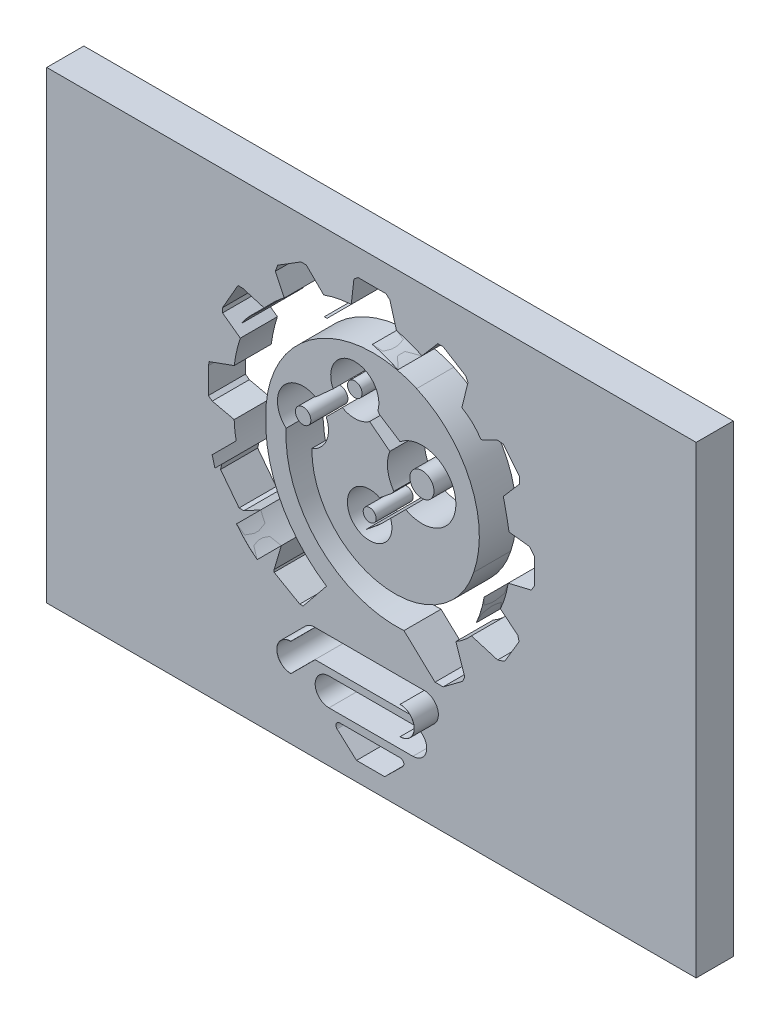
SolidWorks part; units mm, degrees
ref_plane "Front Plane" through (0, 0, 0) normal (0, 0, 1) x (1, 0, 0)
ref_plane "Top Plane" through (0, 0, 0) normal (0, 1, 0) x (1, 0, 0)
ref_plane "Right Plane" through (0, 0, 0) normal (1, 0, 0) x (0, 0, -1)
sketch "Sketch1" plane through (0, 0, 0) normal (0, 0, 1) x (1, 0, 0)
  line L0 (30.4571, 56.7891) -> (92.9051, 56.7891) construction
  line L1 (36.6127, 46.336) -> (66.0639, 46.336) construction
  line L8 (36.6127, 50.1281) -> (66.0639, 50.1281)
  line L11 (36.6127, 42.5438) -> (66.0639, 42.5438)
  line L12 (40.3711, 36.92) -> (62.9922, 36.92) construction
  line L15 (40.3711, 40.6319) -> (62.9922, 40.6319)
  line L16 (40.3711, 33.2082) -> (62.9922, 33.2082)
  line L17 (43.2916, 31.1455) -> (59.5488, 31.1455)
  line L20 (47.7936, 24.6426) -> (55.3803, 24.6426)
  line L21 (60.2553, 29.4313) -> (55.3803, 24.6426)
  line L22 (42.5548, 29.3665) -> (47.7936, 24.6426)
  line L23 (54.0424, 89.0572) -> (57.3383, 91.7453)
  line L24 (56.7754, 86.2384) -> (60.0907, 88.9424)
  line L25 (61.0672, 89.823) -> (60.0907, 88.9424)
  line L26 (57.8581, 92.482) -> (57.3383, 91.7453)
  line L27 (56.7753, 101.2636) -> (51.3382, 105.5029)
  line L28 (59.5486, 104.8905) -> (54.0422, 108.4233)
  line L29 (54.0422, 108.4233) -> (53.5429, 109.1547)
  line L30 (41.4931, 108.2048) -> (36.7513, 103.9283)
  line L31 (43.9752, 105.087) -> (39.6194, 100.7312)
  line L32 (60.5789, 61.3321) -> (68.9548, 53.4849)
  line L33 (71.1414, 53.4849) -> (76.4211, 57.4313)
  line L34 (76.4211, 57.4313) -> (76.9544, 58.7112)
  line L35 (68.9548, 53.4849) -> (71.1414, 53.4849)
  line L36 (76.9544, 58.7112) -> (74.5729, 65.7776)
  line L38 (78.7757, 69.2055) -> (85.8154, 67.0935)
  line L39 (85.8154, 67.0935) -> (87.7229, 67.7364)
  line L40 (87.7229, 67.7364) -> (91.598, 74.2278)
  line L41 (91.598, 74.2278) -> (91.2456, 75.6243)
  line L42 (91.2456, 75.6243) -> (86.565, 79.3976)
  line L44 (88.6833, 86.4585) -> (94.9099, 87.9467)
  line L45 (94.9099, 87.9467) -> (95.7671, 89.3827)
  line L46 (95.7671, 89.3827) -> (95.7671, 96.2119)
  line L47 (95.7671, 96.2119) -> (94.413, 97.8721)
  line L48 (94.413, 97.8721) -> (88.9053, 98.5005)
  line L50 (87.3603, 106.0456) -> (91.6591, 111.0252)
  line L51 (91.6591, 111.0252) -> (91.6591, 112.9758)
  line L52 (91.6591, 112.9758) -> (87.3603, 118.2186)
  line L53 (87.3603, 118.2186) -> (85.8154, 118.3949)
  line L54 (85.8154, 118.3949) -> (81.6957, 116.4107)
  line L55 (81.6957, 116.4107) -> (81.3263, 116.3111)
  line L56 (76.183, 121.1698) -> (77.8389, 127.8606)
  line L57 (77.8389, 127.8606) -> (77.2534, 129.0763)
  line L58 (77.2534, 129.0763) -> (71.1414, 132.8624)
  line L59 (71.1414, 132.8624) -> (69.7035, 132.8624)
  line L60 (69.7035, 132.8624) -> (65.4214, 127.8606)
  line L62 (58.5608, 130.3615) -> (56.7753, 136.6375)
  line L63 (56.7753, 136.6375) -> (55.7168, 137.5437)
  line L64 (55.7168, 137.5437) -> (48.205, 137.5437)
  line L65 (48.205, 137.5437) -> (47.0998, 136.6375)
  line L66 (47.0998, 136.6375) -> (46.3837, 130.3615)
  line L68 (38.9609, 128.8416) -> (34.2686, 133.4995)
  line L69 (34.2686, 133.4995) -> (32.8354, 133.4995)
  line L70 (32.8354, 133.4995) -> (26.5591, 129.6015)
  line L71 (26.5591, 129.6015) -> (25.9244, 127.8606)
  line L72 (25.9244, 127.8606) -> (28.3434, 122.8381)
  line L74 (23.3503, 117.6686) -> (17.1161, 119.5092)
  line L75 (17.1161, 119.5092) -> (15.8505, 119.5092)
  line L76 (15.8505, 119.5092) -> (11.7019, 112.2544)
  line L77 (11.7019, 112.2544) -> (11.7019, 111.0252)
  line L78 (11.7019, 111.0252) -> (16.4833, 107.5433)
  line L80 (14.8364, 100.3097) -> (8.1201, 97.8723)
  line L81 (8.1201, 97.8723) -> (7.8723, 96.7838)
  line L82 (7.8723, 96.7838) -> (7.8723, 89.823)
  line L83 (7.8723, 89.823) -> (8.924, 89.0572)
  line L84 (8.924, 89.0572) -> (14.8364, 87.7111)
  line L86 (16.1477, 80.2776) -> (11.4783, 75.6082)
  line L87 (11.4783, 75.6082) -> (11.164, 74.2278)
  line L88 (11.164, 74.2278) -> (16.1477, 67.7364)
  line L89 (16.1477, 67.7364) -> (17.4483, 67.7364)
  line L90 (17.4483, 67.7364) -> (21.968, 70.1863)
  line L92 (27.5295, 64.6248) -> (25.6004, 58.0911)
  line L93 (25.6004, 58.0911) -> (25.6004, 57.4313)
  line L94 (25.6004, 57.4313) -> (32.5018, 53.4849)
  line L95 (32.5018, 53.4849) -> (33.4122, 53.4849)
  line L96 (33.4122, 53.4849) -> (39.7262, 61.2639)
  arc A4 (36.6127, 50.1281) -> (36.6127, 42.5438) centre (36.6127, 46.336) ccw
  arc A5 (66.0639, 42.5438) -> (66.0639, 50.1281) centre (66.0639, 46.336) ccw
  arc A8 (40.3711, 40.6319) -> (40.3711, 33.2082) centre (40.3711, 36.92) ccw
  arc A9 (62.9922, 33.2082) -> (62.9922, 40.6319) centre (62.9922, 36.92) ccw
  arc A12 (60.2553, 29.4313) -> (59.5488, 31.1455) centre (59.5542, 30.145) ccw
  arc A13 (43.2916, 31.1455) -> (42.5548, 29.3665) centre (43.2916, 30.1034) ccw
  circle A14 centre (51.3383, 83.7011) radius 1.7357
  arc A16 (54.0424, 89.0572) -> (56.7754, 86.2384) centre (51.3383, 83.7011) ccw
  circle A17 centre (65.4214, 97.8721) radius 3.2539
  arc A18 (59.5486, 104.8905) -> (61.0672, 89.823) centre (65.4214, 97.8721) cw
  arc A19 (56.7753, 101.2636) -> (57.8581, 92.482) centre (65.4214, 97.8721) ccw
  circle A20 centre (47.3331, 111.0252) radius 1.9632
  arc A21 (53.5429, 109.1547) -> (41.4931, 108.2048) centre (47.3331, 111.0252) ccw
  arc A22 (51.3382, 105.5029) -> (43.9752, 105.087) centre (47.3331, 111.0252) cw
  circle A23 centre (33.4122, 97.8723) radius 2.0772
  arc A24 (36.7513, 103.9283) -> (28.8345, 92.6889) centre (33.4122, 97.8723) ccw
  arc A25 (39.6194, 100.7312) -> (35.7806, 91.462) centre (33.4122, 97.8723) cw
  arc A26 (28.8345, 92.6889) -> (60.5789, 61.3321) centre (58.5608, 91.0359) ccw
  arc A27 (35.7806, 91.462) -> (79.3675, 84.2956) centre (58.0912, 91.0243) ccw
  arc A28 (79.3675, 84.2956) -> (63.999, 119.5092) centre (52.423, 93.4965) ccw
  arc A29 (63.999, 119.5092) -> (23.3503, 92.7292) centre (52.2487, 93.1048) ccw
  arc A30 (39.7262, 61.2639) -> (23.3503, 92.7292) centre (59.3064, 91.4483) cw
  arc A33 (16.4833, 107.5433) -> (14.8364, 100.3097) centre (52.4804, 95.5437) ccw
  spline S0 degree 2 poles (14.8364, 87.7111) (14.97, 83.7216) (16.1477, 80.2776) knots 0 0 0 1 1 1
  spline S1 degree 2 poles (27.5295, 64.6248) (24.5135, 66.8639) (21.968, 70.1863) knots 0 0 0 1 1 1
  spline S2 degree 2 poles (28.3434, 122.8381) (25.0832, 120.5414) (23.3503, 117.6686) knots 0 0 0 1 1 1
  spline S3 degree 2 poles (46.3837, 130.3615) (43.2077, 130.1934) (38.9609, 128.8416) knots 0 0 0 1 1 1
  spline S4 degree 2 poles (65.4214, 127.8606) (62.7623, 129.3468) (58.5608, 130.3615) knots 0 0 0 1 1 1
  spline S5 degree 2 poles (76.183, 121.1698) (79.2538, 119.4133) (81.3263, 116.3111) knots 0 0 0 1 1 1
  spline S6 degree 1 poles (87.3603, 106.0456) (88.9053, 98.5005) knots 0 0 1 1
  spline S7 degree 2 poles (88.6833, 86.4585) (88.1006, 82.7484) (86.565, 79.3976) knots 0 0 0 1 1 1
  spline S8 degree 2 poles (78.7757, 69.2055) (76.889, 67.188) (74.5729, 65.7776) knots 0 0 0 1 1 1
  point P4 (51.3383, 46.336)
  point P12 (51.6817, 36.92)
extrude "Boss-Extrude1" add sketch "Sketch1" along normal blind 10
sketch "Sketch2" plane through (0, 0, 0) normal (0, 0, -1) x (-1, 0, 0)
  line L1 (-54.14, 86.5559) -> (-58.8145, 90.3685)
  line L2 (-58.8145, 90.3685) -> (-60.3896, 92.6007)
  line L3 (-59.3021, 101.8295) -> (-51.2009, 108.146)
  line L4 (-43.8018, 107.742) -> (-37.0804, 101.0206)
  line L5 (-36.8123, 60.8475) -> (-32.6415, 55.7089)
  line L6 (-32.6415, 55.7089) -> (-32.6415, 55.7089)
  line L7 (-32.6415, 55.7089) -> (-27.7999, 58.4775)
  line L8 (-27.7999, 58.4775) -> (-27.7999, 58.4775)
  line L9 (-27.7999, 58.4775) -> (-29.8561, 65.442)
  line L10 (-22.5558, 72.7799) -> (-17.077, 69.8101)
  line L11 (-17.077, 69.8101) -> (-17.077, 69.8101)
  line L12 (-17.077, 69.8101) -> (-13.3557, 74.6573)
  line L13 (-13.3557, 74.6573) -> (-13.3557, 74.6573)
  line L14 (-13.3557, 74.6573) -> (-18.4724, 79.7739)
  line L15 (-16.8248, 89.3096) -> (-9.8723, 90.8925)
  line L16 (-9.8723, 90.8925) -> (-9.8723, 90.8925)
  line L17 (-9.8723, 90.8925) -> (-9.8723, 96.3806)
  line L18 (-9.8723, 96.3806) -> (-9.8723, 96.3806)
  line L19 (-9.8723, 96.3806) -> (-16.6887, 98.8543)
  line L20 (-18.8683, 108.2807) -> (-13.8311, 111.9488)
  line L21 (-13.8311, 111.9488) -> (-13.8311, 111.9488)
  line L22 (-13.8311, 111.9488) -> (-16.9842, 117.4628)
  line L23 (-16.9842, 117.4628) -> (-16.9842, 117.4628)
  line L24 (-16.9842, 117.4628) -> (-24.3628, 115.2843)
  line L25 (-30.9081, 122.1222) -> (-28.0924, 127.9683)
  line L26 (-28.0924, 127.9683) -> (-28.2014, 128.2672)
  line L27 (-28.2014, 128.2672) -> (-33.4059, 131.4995)
  line L28 (-33.4059, 131.4995) -> (-33.4444, 131.4995)
  line L29 (-33.4444, 131.4995) -> (-38.424, 126.5564)
  line L30 (-48.1674, 128.3526) -> (-48.988, 135.5437)
  line L31 (-48.988, 135.5437) -> (-48.988, 135.5437)
  line L32 (-48.988, 135.5437) -> (-54.9776, 135.5437)
  line L33 (-54.9776, 135.5437) -> (-55.0166, 135.5103)
  line L34 (-55.0166, 135.5103) -> (-56.9612, 128.6751)
  line L35 (-65.8037, 125.2318) -> (-70.6061, 130.8413)
  line L36 (-70.6061, 130.8413) -> (-70.6061, 130.8413)
  line L37 (-70.6061, 130.8413) -> (-75.7045, 127.6831)
  line L38 (-75.7045, 127.6831) -> (-75.7244, 127.6418)
  line L39 (-75.7244, 127.6418) -> (-73.8578, 120.0996)
  line L40 (-80.3979, 113.9894) -> (-82.3959, 114.5281)
  line L41 (-82.3959, 114.5281) -> (-86.1627, 116.3423)
  line L42 (-86.1627, 116.3423) -> (-86.3279, 116.3234)
  line L43 (-86.3279, 116.3234) -> (-89.6591, 112.2607)
  line L44 (-89.6591, 112.2607) -> (-89.6591, 111.769)
  line L45 (-89.6591, 111.769) -> (-85.2037, 106.608)
  line L46 (-85.2037, 106.608) -> (-87.237, 96.6779)
  line L47 (-87.237, 96.6779) -> (-93.3776, 95.9772)
  line L48 (-93.3776, 95.9772) -> (-93.7671, 95.4997)
  line L49 (-93.7671, 95.4997) -> (-93.7671, 89.9342)
  line L50 (-93.7671, 89.9342) -> (-93.6248, 89.6959)
  line L51 (-93.6248, 89.6959) -> (-86.8806, 88.0839)
  line L52 (-84.0603, 78.8479) -> (-89.4385, 74.5121)
  line L53 (-89.4385, 74.5121) -> (-89.4385, 74.5121)
  line L54 (-89.4385, 74.5121) -> (-86.3843, 69.3958)
  line L55 (-86.3843, 69.3958) -> (-85.7801, 69.1922)
  line L56 (-85.7801, 69.1922) -> (-78.1209, 71.49)
  line L57 (-72.1441, 66.722) -> (-74.8187, 58.7857)
  line L58 (-74.8187, 58.7857) -> (-74.7854, 58.7056)
  line L59 (-74.7854, 58.7056) -> (-70.4765, 55.4849)
  line L60 (-70.4765, 55.4849) -> (-69.7453, 55.4849)
  line L61 (-69.7453, 55.4849) -> (-61.2981, 63.3988)
  line L62 (-36.8826, 101.3536) -> (-44.1277, 107.8876)
  line L63 (-51.2885, 108.91) -> (-52.6198, 106.9596)
  line L64 (-52.6198, 106.9596) -> (-59.8316, 102.3327)
  line L65 (-60.8803, 92.3476) -> (-58.7881, 90.4609)
  line L66 (-58.7881, 90.4609) -> (-54.0759, 86.6175)
  line L67 (-54.0424, 89.0572) -> (-57.3383, 91.7453)
  line L68 (-57.3383, 91.7453) -> (-57.8581, 92.482)
  line L69 (-56.7753, 101.2636) -> (-51.3382, 105.5029)
  line L70 (-43.9752, 105.087) -> (-39.6194, 100.7312)
  line L71 (-39.7262, 61.2639) -> (-33.4122, 53.4849)
  line L72 (-33.4122, 53.4849) -> (-32.5018, 53.4849)
  line L73 (-32.5018, 53.4849) -> (-25.6004, 57.4313)
  line L74 (-25.6004, 57.4313) -> (-25.6004, 58.0911)
  line L75 (-25.6004, 58.0911) -> (-27.5295, 64.6248)
  line L76 (-21.968, 70.1863) -> (-17.4483, 67.7364)
  line L77 (-17.4483, 67.7364) -> (-16.1477, 67.7364)
  line L78 (-16.1477, 67.7364) -> (-11.164, 74.2278)
  line L79 (-11.164, 74.2278) -> (-11.4783, 75.6082)
  line L80 (-11.4783, 75.6082) -> (-16.1477, 80.2776)
  line L81 (-14.8364, 87.7111) -> (-8.924, 89.0572)
  line L82 (-8.924, 89.0572) -> (-7.8723, 89.823)
  line L83 (-7.8723, 89.823) -> (-7.8723, 96.7838)
  line L84 (-7.8723, 96.7838) -> (-8.1201, 97.8723)
  line L85 (-8.1201, 97.8723) -> (-14.8364, 100.3097)
  line L86 (-16.4833, 107.5433) -> (-11.7019, 111.0252)
  line L87 (-11.7019, 111.0252) -> (-11.7019, 112.2544)
  line L88 (-11.7019, 112.2544) -> (-15.8505, 119.5092)
  line L89 (-15.8505, 119.5092) -> (-17.1161, 119.5092)
  line L90 (-17.1161, 119.5092) -> (-23.3503, 117.6686)
  line L91 (-28.3434, 122.8381) -> (-25.9244, 127.8606)
  line L92 (-25.9244, 127.8606) -> (-26.5591, 129.6015)
  line L93 (-26.5591, 129.6015) -> (-32.8354, 133.4995)
  line L94 (-32.8354, 133.4995) -> (-34.2686, 133.4995)
  line L95 (-34.2686, 133.4995) -> (-38.9609, 128.8416)
  line L96 (-46.3837, 130.3615) -> (-47.0998, 136.6375)
  line L97 (-47.0998, 136.6375) -> (-48.205, 137.5437)
  line L98 (-48.205, 137.5437) -> (-55.7168, 137.5437)
  line L99 (-55.7168, 137.5437) -> (-56.7753, 136.6375)
  line L100 (-56.7753, 136.6375) -> (-58.5608, 130.3615)
  line L101 (-65.4214, 127.8606) -> (-69.7035, 132.8624)
  line L102 (-69.7035, 132.8624) -> (-71.1414, 132.8624)
  line L103 (-71.1414, 132.8624) -> (-77.2534, 129.0763)
  line L104 (-77.2534, 129.0763) -> (-77.8389, 127.8606)
  line L105 (-77.8389, 127.8606) -> (-76.183, 121.1698)
  line L106 (-81.3263, 116.3111) -> (-81.6957, 116.4107)
  line L107 (-81.6957, 116.4107) -> (-85.8154, 118.3949)
  line L108 (-85.8154, 118.3949) -> (-87.3603, 118.2186)
  line L109 (-87.3603, 118.2186) -> (-91.6591, 112.9758)
  line L110 (-91.6591, 112.9758) -> (-91.6591, 111.0252)
  line L111 (-91.6591, 111.0252) -> (-87.3603, 106.0456)
  line L112 (-87.3603, 106.0456) -> (-88.9053, 98.5005)
  line L113 (-88.9053, 98.5005) -> (-94.413, 97.8721)
  line L114 (-94.413, 97.8721) -> (-95.7671, 96.2119)
  line L115 (-95.7671, 96.2119) -> (-95.7671, 89.3827)
  line L116 (-95.7671, 89.3827) -> (-94.9099, 87.9467)
  line L117 (-94.9099, 87.9467) -> (-88.6833, 86.4585)
  line L118 (-86.565, 79.3976) -> (-91.2456, 75.6243)
  line L119 (-91.2456, 75.6243) -> (-91.598, 74.2278)
  line L120 (-91.598, 74.2278) -> (-87.7229, 67.7364)
  line L121 (-87.7229, 67.7364) -> (-85.8154, 67.0935)
  line L122 (-85.8154, 67.0935) -> (-78.7757, 69.2055)
  line L123 (-74.5729, 65.7776) -> (-76.9544, 58.7112)
  line L124 (-76.9544, 58.7112) -> (-76.4211, 57.4313)
  line L125 (-76.4211, 57.4313) -> (-71.1414, 53.4849)
  line L126 (-71.1414, 53.4849) -> (-68.9548, 53.4849)
  line L127 (-68.9548, 53.4849) -> (-60.5789, 61.3321)
  line L128 (-36.7513, 103.9283) -> (-41.4931, 108.2048)
  line L129 (-53.5429, 109.1547) -> (-54.0422, 108.4233)
  line L130 (-54.0422, 108.4233) -> (-59.5486, 104.8905)
  line L131 (-61.0672, 89.823) -> (-60.0907, 88.9424)
  line L132 (-60.0907, 88.9424) -> (-56.7754, 86.2384)
  line L133 (-54.0424, 89.0572) -> (-57.3383, 91.7453)
  line L134 (-57.3383, 91.7453) -> (-57.8581, 92.482)
  line L135 (-56.7753, 101.2636) -> (-51.3382, 105.5029)
  line L136 (-43.9752, 105.087) -> (-39.6194, 100.7312)
  line L137 (-39.7262, 61.2639) -> (-33.4122, 53.4849)
  line L138 (-33.4122, 53.4849) -> (-32.5018, 53.4849)
  line L139 (-32.5018, 53.4849) -> (-25.6004, 57.4313)
  line L140 (-25.6004, 57.4313) -> (-25.6004, 58.0911)
  line L141 (-25.6004, 58.0911) -> (-27.5295, 64.6248)
  line L142 (-21.968, 70.1863) -> (-17.4483, 67.7364)
  line L143 (-17.4483, 67.7364) -> (-16.1477, 67.7364)
  line L144 (-16.1477, 67.7364) -> (-11.164, 74.2278)
  line L145 (-11.164, 74.2278) -> (-11.4783, 75.6082)
  line L146 (-11.4783, 75.6082) -> (-16.1477, 80.2776)
  line L147 (-14.8364, 87.7111) -> (-8.924, 89.0572)
  line L148 (-8.924, 89.0572) -> (-7.8723, 89.823)
  line L149 (-7.8723, 89.823) -> (-7.8723, 96.7838)
  line L150 (-7.8723, 96.7838) -> (-8.1201, 97.8723)
  line L151 (-8.1201, 97.8723) -> (-14.8364, 100.3097)
  line L152 (-16.4833, 107.5433) -> (-11.7019, 111.0252)
  line L153 (-11.7019, 111.0252) -> (-11.7019, 112.2544)
  line L154 (-11.7019, 112.2544) -> (-15.8505, 119.5092)
  line L155 (-15.8505, 119.5092) -> (-17.1161, 119.5092)
  line L156 (-17.1161, 119.5092) -> (-23.3503, 117.6686)
  line L157 (-28.3434, 122.8381) -> (-25.9244, 127.8606)
  line L158 (-25.9244, 127.8606) -> (-26.5591, 129.6015)
  line L159 (-26.5591, 129.6015) -> (-32.8354, 133.4995)
  line L160 (-32.8354, 133.4995) -> (-34.2686, 133.4995)
  line L161 (-34.2686, 133.4995) -> (-38.9609, 128.8416)
  line L162 (-46.3837, 130.3615) -> (-47.0998, 136.6375)
  line L163 (-47.0998, 136.6375) -> (-48.205, 137.5437)
  line L164 (-48.205, 137.5437) -> (-55.7168, 137.5437)
  line L165 (-55.7168, 137.5437) -> (-56.7753, 136.6375)
  line L166 (-56.7753, 136.6375) -> (-58.5608, 130.3615)
  line L167 (-65.4214, 127.8606) -> (-69.7035, 132.8624)
  line L168 (-69.7035, 132.8624) -> (-71.1414, 132.8624)
  line L169 (-71.1414, 132.8624) -> (-77.2534, 129.0763)
  line L170 (-77.2534, 129.0763) -> (-77.8389, 127.8606)
  line L171 (-77.8389, 127.8606) -> (-76.183, 121.1698)
  line L172 (-81.3263, 116.3111) -> (-81.6957, 116.4107)
  line L173 (-81.6957, 116.4107) -> (-85.8154, 118.3949)
  line L174 (-85.8154, 118.3949) -> (-87.3603, 118.2186)
  line L175 (-87.3603, 118.2186) -> (-91.6591, 112.9758)
  line L176 (-91.6591, 112.9758) -> (-91.6591, 111.0252)
  line L177 (-91.6591, 111.0252) -> (-87.3603, 106.0456)
  line L178 (-87.3603, 106.0456) -> (-88.9053, 98.5005)
  line L179 (-88.9053, 98.5005) -> (-94.413, 97.8721)
  line L180 (-94.413, 97.8721) -> (-95.7671, 96.2119)
  line L181 (-95.7671, 96.2119) -> (-95.7671, 89.3827)
  line L182 (-95.7671, 89.3827) -> (-94.9099, 87.9467)
  line L183 (-94.9099, 87.9467) -> (-88.6833, 86.4585)
  line L184 (-86.565, 79.3976) -> (-91.2456, 75.6243)
  line L185 (-91.2456, 75.6243) -> (-91.598, 74.2278)
  line L186 (-91.598, 74.2278) -> (-87.7229, 67.7364)
  line L187 (-87.7229, 67.7364) -> (-85.8154, 67.0935)
  line L188 (-85.8154, 67.0935) -> (-78.7757, 69.2055)
  line L189 (-74.5729, 65.7776) -> (-76.9544, 58.7112)
  line L190 (-76.9544, 58.7112) -> (-76.4211, 57.4313)
  line L191 (-76.4211, 57.4313) -> (-71.1414, 53.4849)
  line L192 (-71.1414, 53.4849) -> (-68.9548, 53.4849)
  line L193 (-68.9548, 53.4849) -> (-60.5789, 61.3321)
  line L194 (-36.7513, 103.9283) -> (-41.4931, 108.2048)
  line L195 (-53.5429, 109.1547) -> (-54.0422, 108.4233)
  line L196 (-54.0422, 108.4233) -> (-59.5486, 104.8905)
  line L197 (-61.0672, 89.823) -> (-60.0907, 88.9424)
  line L198 (-60.0907, 88.9424) -> (-56.7754, 86.2384)
  arc A0 (-54.0759, 86.6175) -> (-54.14, 86.5559) centre (-51.3383, 83.7011) ccw
  arc A1 (-60.3896, 92.6007) -> (-59.3021, 101.8295) centre (-65.4214, 97.8721) ccw
  arc A2 (-51.2009, 108.146) -> (-43.8018, 107.742) centre (-47.3331, 111.0252) ccw
  arc A3 (-37.0804, 101.0206) -> (-33.8616, 93.0594) centre (-33.4122, 97.8723) ccw
  arc A4 (-81.2676, 83.6708) -> (-33.8616, 93.0594) centre (-58.0912, 91.0243) ccw
  arc A5 (-64.8122, 121.3364) -> (-81.2676, 83.6708) centre (-52.423, 93.4965) ccw
  arc A6 (-21.3499, 92.752) -> (-64.8122, 121.3364) centre (-52.2487, 93.1048) ccw
  arc A7 (-36.8123, 60.8475) -> (-21.3499, 92.752) centre (-59.3064, 91.4483) ccw
  arc A8 (-16.6887, 98.8543) -> (-18.8683, 108.2807) centre (-52.4804, 95.5437) ccw
  arc A9 (-61.2981, 63.3988) -> (-30.911, 93.6408) centre (-58.5608, 91.0359) ccw
  arc A10 (-30.911, 93.6408) -> (-36.8826, 101.3536) centre (-33.4122, 97.8723) ccw
  arc A11 (-44.1277, 107.8876) -> (-51.2885, 108.91) centre (-47.3331, 111.0252) ccw
  arc A12 (-59.8316, 102.3327) -> (-60.8803, 92.3476) centre (-65.4214, 97.8721) ccw
  arc A13 (-56.7754, 86.2384) -> (-54.0424, 89.0572) centre (-51.3383, 83.7011) ccw
  arc A14 (-57.8581, 92.482) -> (-56.7753, 101.2636) centre (-65.4214, 97.8721) ccw
  arc A15 (-51.3382, 105.5029) -> (-43.9752, 105.087) centre (-47.3331, 111.0252) ccw
  arc A16 (-39.6194, 100.7312) -> (-35.7806, 91.462) centre (-33.4122, 97.8723) ccw
  arc A17 (-79.3675, 84.2956) -> (-35.7806, 91.462) centre (-58.0912, 91.0243) ccw
  arc A18 (-63.999, 119.5092) -> (-79.3675, 84.2956) centre (-52.423, 93.4965) ccw
  arc A19 (-23.3503, 92.7292) -> (-63.999, 119.5092) centre (-52.2487, 93.1048) ccw
  arc A20 (-39.7262, 61.2639) -> (-23.3503, 92.7292) centre (-59.3064, 91.4483) ccw
  arc A21 (-14.8364, 100.3097) -> (-16.4833, 107.5433) centre (-52.4804, 95.5437) ccw
  arc A22 (-60.5789, 61.3321) -> (-28.8345, 92.6889) centre (-58.5608, 91.0359) ccw
  arc A23 (-28.8345, 92.6889) -> (-36.7513, 103.9283) centre (-33.4122, 97.8723) ccw
  arc A24 (-41.4931, 108.2048) -> (-53.5429, 109.1547) centre (-47.3331, 111.0252) ccw
  arc A25 (-59.5486, 104.8905) -> (-61.0672, 89.823) centre (-65.4214, 97.8721) ccw
  arc A26 (-56.7754, 86.2384) -> (-54.0424, 89.0572) centre (-51.3383, 83.7011) ccw
  arc A27 (-57.8581, 92.482) -> (-56.7753, 101.2636) centre (-65.4214, 97.8721) ccw
  arc A28 (-51.3382, 105.5029) -> (-43.9752, 105.087) centre (-47.3331, 111.0252) ccw
  arc A29 (-39.6194, 100.7312) -> (-35.7806, 91.462) centre (-33.4122, 97.8723) ccw
  arc A30 (-79.3675, 84.2956) -> (-35.7806, 91.462) centre (-58.0912, 91.0243) ccw
  arc A31 (-63.999, 119.5092) -> (-79.3675, 84.2956) centre (-52.423, 93.4965) ccw
  arc A32 (-23.3503, 92.7292) -> (-63.999, 119.5092) centre (-52.2487, 93.1048) ccw
  arc A33 (-39.7262, 61.2639) -> (-23.3503, 92.7292) centre (-59.3064, 91.4483) ccw
  arc A34 (-14.8364, 100.3097) -> (-16.4833, 107.5433) centre (-52.4804, 95.5437) ccw
  arc A35 (-60.5789, 61.3321) -> (-28.8345, 92.6889) centre (-58.5608, 91.0359) ccw
  arc A36 (-28.8345, 92.6889) -> (-36.7513, 103.9283) centre (-33.4122, 97.8723) ccw
  arc A37 (-41.4931, 108.2048) -> (-53.5429, 109.1547) centre (-47.3331, 111.0252) ccw
  arc A38 (-59.5486, 104.8905) -> (-61.0672, 89.823) centre (-65.4214, 97.8721) ccw
  parabola Q8 (-27.5295, 64.6248) -> (-21.968, 70.1863) focus (-36.6411, 72.3496) apex (-32.1285, 61.957)
  parabola Q9 (-16.1477, 80.2776) -> (-14.8364, 87.7111) focus (-27.2163, 82.2633) apex (-17.4778, 77.1751)
  parabola Q10 (-23.3503, 117.6686) -> (-28.3434, 122.8381) focus (-28.5124, 113.0969) apex (-22.2722, 115.4509)
  parabola Q11 (-38.9609, 128.8416) -> (-46.3837, 130.3615) focus (-51.1069, 126.1376) apex (-53.2201, 128.4735)
  parabola Q12 (-58.5608, 130.3615) -> (-65.4214, 127.8606) focus (-66.8713, 122.2923) apex (-69.7381, 123.1689)
  parabola Q13 (-76.183, 121.1698) -> (-81.3263, 116.3111) focus (-73.2684, 114.293) apex (-77.656, 120.2074)
  parabola Q14 (-88.6833, 86.4585) -> (-86.565, 79.3976) focus (-74.8514, 85.7796) apex (-87.2732, 81.0955)
  parabola Q15 (-78.7757, 69.2055) -> (-74.5729, 65.7776) focus (-70.0201, 74.5575) apex (-75.7041, 66.5208)
  parabola Q16 (-27.5295, 64.6248) -> (-21.968, 70.1863) focus (-36.6411, 72.3496) apex (-32.1285, 61.957)
  parabola Q17 (-16.1477, 80.2776) -> (-14.8364, 87.7111) focus (-27.2163, 82.2633) apex (-17.4778, 77.1751)
  parabola Q18 (-23.3503, 117.6686) -> (-28.3434, 122.8381) focus (-28.5124, 113.0969) apex (-22.2722, 115.4509)
  parabola Q19 (-38.9609, 128.8416) -> (-46.3837, 130.3615) focus (-51.1069, 126.1376) apex (-53.2201, 128.4735)
  parabola Q20 (-58.5608, 130.3615) -> (-65.4214, 127.8606) focus (-66.8713, 122.2923) apex (-69.7381, 123.1689)
  parabola Q21 (-76.183, 121.1698) -> (-81.3263, 116.3111) focus (-73.2684, 114.293) apex (-77.656, 120.2074)
  parabola Q22 (-88.6833, 86.4585) -> (-86.565, 79.3976) focus (-74.8514, 85.7796) apex (-87.2732, 81.0955)
  parabola Q23 (-78.7757, 69.2055) -> (-74.5729, 65.7776) focus (-70.0201, 74.5575) apex (-75.7041, 66.5208)
  spline S0 degree 1 poles (-29.8561, 65.442) (-22.5558, 72.7799) knots 0 0 1 1 construction
  spline S1 degree 1 poles (-18.4724, 79.7739) (-16.8248, 89.3096) knots 0 0 1 1 construction
  spline S2 degree 1 poles (-24.3628, 115.2843) (-30.9081, 122.1222) knots 0 0 1 1 construction
  spline S3 degree 1 poles (-38.424, 126.5564) (-48.1674, 128.3526) knots 0 0 1 1 construction
  spline S4 degree 1 poles (-56.9612, 128.6751) (-65.8037, 125.2318) knots 0 0 1 1 construction
  spline S5 degree 1 poles (-73.8578, 120.0996) (-80.3979, 113.9894) knots 0 0 1 1 construction
  spline S6 degree 1 poles (-86.8806, 88.0839) (-84.0603, 78.8479) knots 0 0 1 1 construction
  spline S7 degree 1 poles (-78.1209, 71.49) (-72.1441, 66.722) knots 0 0 1 1 construction
  spline S8 degree 3 poles (-29.8561, 65.442) (-29.1755, 65.884) (-27.8791, 66.8318) (-26.0024, 68.5312) (-24.5199, 70.1696) (-23.3838, 71.612) (-22.8245, 72.3896) (-22.5558, 72.7799) knots 0.500282 0.500282 0.500282 0.500282 0.500475 0.500667 0.500859 0.500955 0.501051 0.501051 0.501051 0.501051
  spline S9 degree 3 poles (-18.4724, 79.7739) (-18.1809, 80.4842) (-17.6821, 81.9251) (-17.1525, 84.2374) (-16.9031, 86.281) (-16.8191, 87.9836) (-16.8164, 88.8707) (-16.8248, 89.3096) knots 0.500153 0.500153 0.500153 0.500153 0.500341 0.50053 0.500718 0.500812 0.500906 0.500906 0.500906 0.500906
  spline S10 degree 3 poles (-24.3628, 115.2843) (-24.6467, 115.9337) (-25.3222, 117.1593) (-26.735, 118.9215) (-28.2635, 120.3079) (-29.6944, 121.3595) (-30.5042, 121.879) (-30.9081, 122.1222) knots 0.500066 0.500066 0.500066 0.500066 0.500305 0.500543 0.500781 0.5009 0.501019 0.501019 0.501019 0.501019
  spline S11 degree 3 poles (-38.424, 126.5564) (-38.9237, 126.7287) (-39.9513, 127.0654) (-41.8435, 127.6142) (-44.0285, 128.1106) (-45.9197, 128.35) (-47.2723, 128.3963) (-47.8625, 128.3756) (-48.1674, 128.3526) knots 0.498389 0.498389 0.498389 0.498389 0.498504 0.498619 0.49885 0.49908 0.499196 0.499311 0.499311 0.499311 0.499311
  spline S12 degree 3 poles (-56.9612, 128.6751) (-57.464, 128.5668) (-58.4903, 128.3285) (-60.3332, 127.8285) (-62.3772, 127.1332) (-64.0252, 126.3705) (-65.1246, 125.7212) (-65.5766, 125.4058) (-65.8037, 125.2318) knots 0.498448 0.498448 0.498448 0.498448 0.498565 0.498681 0.498915 0.499148 0.499264 0.499381 0.499381 0.499381 0.499381
  spline S13 degree 3 poles (-73.8578, 120.0996) (-74.5416, 119.8034) (-75.8747, 119.0902) (-77.5953, 117.7419) (-78.8646, 116.3448) (-79.7724, 115.063) (-80.2001, 114.3485) (-80.3979, 113.9894) knots 0.499683 0.499683 0.499683 0.499683 0.499917 0.500152 0.500386 0.500504 0.500621 0.500621 0.500621 0.500621
  spline S14 degree 3 poles (-86.8806, 88.0839) (-86.7933, 87.2651) (-86.5412, 85.622) (-85.9467, 83.2789) (-85.1338, 81.0177) (-84.4403, 79.5575) (-84.0603, 78.8479) knots 0.499526 0.499526 0.499526 0.499526 0.499705 0.499883 0.500062 0.50024 0.50024 0.50024 0.50024
  spline S15 degree 3 poles (-78.1209, 71.49) (-77.7049, 70.985) (-76.8135, 70.0072) (-75.3833, 68.7382) (-73.837, 67.6345) (-72.7167, 67.0052) (-72.1441, 66.722) knots 0.499572 0.499572 0.499572 0.499572 0.499741 0.49991 0.500078 0.500247 0.500247 0.500247 0.500247
  dimension "D1" = 0
  dimension "D2" = 2
extrude "Cut-Extrude2" cut sketch "Sketch2" against normal blind 3.5 contours L56 S15 L57 L58 L59 L60 L61 A9 A10 L62 L4 A3 A4 A5 A6 A7 L5 L7 L9 S8 L10 L12 L14 S9 L15 L17 L19 A8 L20 L22 L24 S10 L25 L26 L27 L28 L29 S11 L30 L32 L33 L34 S12 L35 L37 L38 L39 S13 L40 L41 L42
sketch "Sketch3" plane through (0, 0, 3.5) normal (0, 0, -1) x (-1, 0, 0)
  line L0 (-95.7671, 89.3827) -> (-95.7671, 96.2119) construction
  line L1 (35.6779, 144.6308) -> (-139.3221, 144.6308)
  line L2 (35.6779, 144.6308) -> (35.6779, 19.6308)
  line L3 (35.6779, 19.6308) -> (-139.3221, 19.6308)
  line L4 (-139.3221, 144.6308) -> (-139.3221, 19.6308)
  dimension "D1" = 125
  dimension "D2" = 175
  dimension "D3" = 43.555
extrude "Boss-Extrude2" add sketch "Sketch3" along normal blind 10
sketch "Sketch4" plane through (0, 0, 10) normal (0, 0, 1) x (1, 0, 0)
  line L0 (62.9922, 36.92) -> (40.3711, 36.92) construction
  line L2 (95.7671, 96.2119) -> (95.7671, 89.3827)
  line L3 (95.7671, 89.3827) -> (94.9099, 87.9467)
  line L4 (94.9099, 87.9467) -> (88.6833, 86.4585)
  line L5 (95.7671, 96.2119) -> (94.413, 97.8721)
  line L6 (94.413, 97.8721) -> (88.9053, 98.5005)
  line L7 (86.565, 79.3976) -> (91.2456, 75.6243)
  line L8 (91.2456, 75.6243) -> (91.598, 74.2278)
  line L9 (91.598, 74.2278) -> (87.7229, 67.7364)
  line L10 (87.7229, 67.7364) -> (85.8154, 67.0935)
  line L11 (85.8154, 67.0935) -> (78.7757, 69.2055)
  line L12 (74.5729, 65.7776) -> (76.9544, 58.7112)
  line L13 (76.9544, 58.7112) -> (76.4211, 57.4313)
  line L14 (76.4211, 57.4313) -> (71.1414, 53.4849)
  line L15 (71.1414, 53.4849) -> (68.9548, 53.4849)
  line L16 (68.9548, 53.4849) -> (60.5789, 61.3321)
  line L17 (39.7262, 61.2639) -> (33.4122, 53.4849)
  line L18 (33.4122, 53.4849) -> (32.5018, 53.4849)
  line L19 (32.5018, 53.4849) -> (25.6004, 57.4313)
  line L20 (25.6004, 57.4313) -> (25.6004, 58.0911)
  line L21 (25.6004, 58.0911) -> (27.5295, 64.6248)
  line L22 (21.968, 70.1863) -> (17.4483, 67.7364)
  line L23 (17.4483, 67.7364) -> (16.1477, 67.7364)
  line L24 (16.1477, 67.7364) -> (11.164, 74.2278)
  line L25 (11.164, 74.2278) -> (11.4783, 75.6082)
  line L26 (11.4783, 75.6082) -> (16.1477, 80.2776)
  line L27 (14.8364, 87.7111) -> (8.924, 89.0572)
  line L28 (8.924, 89.0572) -> (7.8723, 89.823)
  line L29 (7.8723, 89.823) -> (7.8723, 96.7838)
  line L30 (7.8723, 96.7838) -> (8.1201, 97.8723)
  line L31 (8.1201, 97.8723) -> (14.8364, 100.3097)
  line L33 (11.7019, 111.0252) -> (11.7019, 112.2544)
  line L34 (11.7019, 112.2544) -> (15.8505, 119.5092)
  line L35 (15.8505, 119.5092) -> (17.1161, 119.5092)
  line L36 (17.1161, 119.5092) -> (23.3503, 117.6686)
  line L37 (28.3434, 122.8381) -> (25.9244, 127.8606)
  line L38 (25.9244, 127.8606) -> (26.5591, 129.6015)
  line L39 (26.5591, 129.6015) -> (32.8354, 133.4995)
  line L40 (32.8354, 133.4995) -> (34.2686, 133.4995)
  line L41 (34.2686, 133.4995) -> (38.9609, 128.8416)
  line L42 (46.3837, 130.3615) -> (47.0998, 136.6375)
  line L43 (47.0998, 136.6375) -> (48.205, 137.5437)
  line L44 (48.205, 137.5437) -> (55.7168, 137.5437)
  line L45 (55.7168, 137.5437) -> (56.7753, 136.6375)
  line L46 (56.7753, 136.6375) -> (58.5608, 130.3615)
  line L47 (65.4214, 127.8606) -> (69.7035, 132.8624)
  line L48 (69.7035, 132.8624) -> (71.1414, 132.8624)
  line L49 (71.1414, 132.8624) -> (77.2534, 129.0763)
  line L50 (77.2534, 129.0763) -> (77.8389, 127.8606)
  line L51 (77.8389, 127.8606) -> (76.183, 121.1698)
  line L52 (87.3603, 106.0456) -> (91.6591, 111.0252)
  line L53 (91.6591, 111.0252) -> (91.6591, 112.9758)
  line L54 (91.6591, 112.9758) -> (87.3603, 118.2186)
  line L55 (87.3603, 118.2186) -> (85.8154, 118.3949)
  line L56 (85.8154, 118.3949) -> (81.6957, 116.4107)
  line L57 (81.3263, 116.3111) -> (81.6957, 116.4107)
  line L58 (55.3803, 24.6426) -> (47.7936, 24.6426)
  line L59 (47.7936, 24.6426) -> (42.5548, 29.3665)
  line L60 (43.2916, 31.1455) -> (59.5488, 31.1455)
  line L61 (60.2553, 29.4313) -> (55.3803, 24.6426)
  line L62 (60.0907, 88.9424) -> (61.0672, 89.823) construction
  line L63 (57.3383, 91.7453) -> (57.8581, 92.482) construction
  line L64 (66.0639, 46.3354) -> (36.6127, 46.3354) construction
  line L65 (66.0639, 42.5756) -> (36.6127, 42.5756)
  line L66 (66.0639, 50.0953) -> (36.6127, 50.0953)
  line L68 (62.9922, 33.2049) -> (40.3711, 33.2049)
  line L69 (62.9922, 40.6352) -> (40.3711, 40.6352)
  line L70 (43.9752, 105.087) -> (39.6194, 100.7312) construction
  line L71 (43.9752, 105.087) -> (39.6194, 100.7312)
  line L72 (41.4931, 108.2048) -> (36.7513, 103.9283)
  line L73 (53.5429, 109.1547) -> (54.0422, 108.4233)
  line L74 (54.0422, 108.4233) -> (59.5486, 104.8905)
  line L75 (51.3382, 105.5029) -> (56.7753, 101.2636)
  line L76 (56.7754, 86.2384) -> (61.0672, 89.823)
  line L78 (54.0424, 89.0572) -> (57.3383, 91.7453)
  line L79 (57.8581, 92.482) -> (57.3383, 91.7453)
  line L80 (11.7019, 111.0252) -> (16.4833, 107.5433)
  arc A0 (66.0639, 42.5756) -> (66.0639, 50.0953) centre (66.0639, 46.3354) ccw
  arc A1 (36.6127, 50.0953) -> (36.6127, 42.5756) centre (36.6127, 46.3354) ccw
  arc A4 (62.9922, 33.2049) -> (62.9922, 40.6352) centre (62.9922, 36.92) ccw
  arc A5 (40.3711, 40.6352) -> (40.3711, 33.2049) centre (40.3711, 36.92) ccw
  arc A6 (59.5488, 31.1455) -> (60.2553, 29.4313) centre (59.5488, 30.1428) cw
  arc A8 (42.5548, 29.3665) -> (43.2916, 31.1455) centre (43.2916, 30.1034) cw
  circle A9 centre (33.4122, 97.8723) radius 2.0772
  circle A10 centre (47.3331, 111.0252) radius 1.9632
  circle A11 centre (65.4214, 97.8721) radius 3.2539
  circle A13 centre (51.3383, 83.7011) radius 1.7357
  arc A17 (54.0424, 89.0572) -> (56.7754, 86.2384) centre (51.3383, 83.7011) ccw
  arc A18 (54.0424, 89.0572) -> (56.7754, 86.2384) centre (51.3383, 83.7011) ccw construction
  arc A19 (59.5486, 104.8905) -> (61.0672, 89.823) centre (65.4214, 97.8721) cw
  arc A20 (56.7753, 101.2636) -> (57.8581, 92.482) centre (65.4214, 97.8721) ccw
  arc A21 (56.7753, 101.2636) -> (57.8581, 92.482) centre (65.4214, 97.8721) ccw construction
  arc A22 (56.7753, 101.2636) -> (57.8581, 92.482) centre (65.4214, 97.8721) ccw construction
  arc A23 (53.5429, 109.1547) -> (41.4931, 108.2048) centre (47.3331, 111.0252) ccw
  arc A24 (51.3382, 105.5029) -> (43.9752, 105.087) centre (47.3331, 111.0252) cw
  arc A26 (36.7513, 103.9283) -> (28.8345, 92.6889) centre (33.4122, 97.8723) ccw
  arc A27 (28.8345, 92.6889) -> (60.5789, 61.3321) centre (58.5608, 91.0359) ccw construction
  arc A28 (39.6194, 100.7312) -> (35.7806, 91.462) centre (33.4122, 97.8723) cw
  arc A29 (35.7806, 91.462) -> (39.6194, 100.7312) centre (33.4122, 97.8723) ccw construction
  arc A30 (35.7806, 91.462) -> (39.6194, 100.7312) centre (33.4122, 97.8723) ccw construction
  arc A32 (58.5608, 130.3615) -> (65.4214, 127.8606) centre (50.8878, 98.6518) cw
  arc A33 (76.183, 121.1698) -> (81.3263, 116.3111) centre (68.8026, 108.2053) cw
  arc A34 (87.3603, 106.0456) -> (88.9053, 98.5005) centre (-37.3015, 76.5889) cw
  arc A35 (88.6833, 86.4585) -> (86.565, 79.3976) centre (60.2964, 91.1266) cw
  arc A36 (78.7757, 69.2055) -> (74.5729, 65.7776) centre (66.1629, 80.3796) cw
  arc A37 (46.3837, 130.3615) -> (38.9609, 128.8416) centre (47.9579, 103.7882) ccw
  arc A38 (28.3434, 122.8381) -> (23.3503, 117.6686) centre (38.9914, 107.5573) ccw
  arc A39 (16.4833, 107.5433) -> (14.8364, 100.3097) centre (52.4804, 95.5437) ccw
  arc A40 (14.8364, 87.7111) -> (16.1477, 80.2776) centre (40.0614, 88.3283) ccw
  arc A41 (21.968, 70.1863) -> (27.5295, 64.6248) centre (46.6119, 89.2687) ccw
  arc A42 (35.7806, 91.462) -> (79.3675, 84.2956) centre (58.0912, 91.0243) ccw
  arc A43 (79.3675, 84.2956) -> (63.999, 119.5092) centre (52.423, 93.4965) ccw
  arc A44 (63.999, 119.5092) -> (23.3503, 92.7292) centre (52.2487, 93.1048) ccw
  arc A45 (23.3503, 92.7292) -> (39.7262, 61.2639) centre (59.3064, 91.4483) ccw
  arc A46 (60.5789, 61.3321) -> (28.8345, 92.6889) centre (58.5608, 91.0359) cw
  point P4 (51.6817, 36.92)
  point P165 (51.3383, 46.3354)
extrude "Cut-Extrude3" cut sketch "Sketch4" against normal blind 56
sketch "Sketch5" plane through (0, 50.1281, 0) normal (0, 1, 0) x (1, 0, 0)
  line L1 (36.6127, -10) -> (66.0639, -10)
  line L2 (36.6127, -10) -> (36.6127, -3.5)
  line L3 (36.6127, -3.5) -> (66.0639, -3.5)
  line L4 (66.0639, -10) -> (66.0639, -3.5)
extrude "Cut-Extrude4" cut sketch "Sketch5" against normal blind 50
